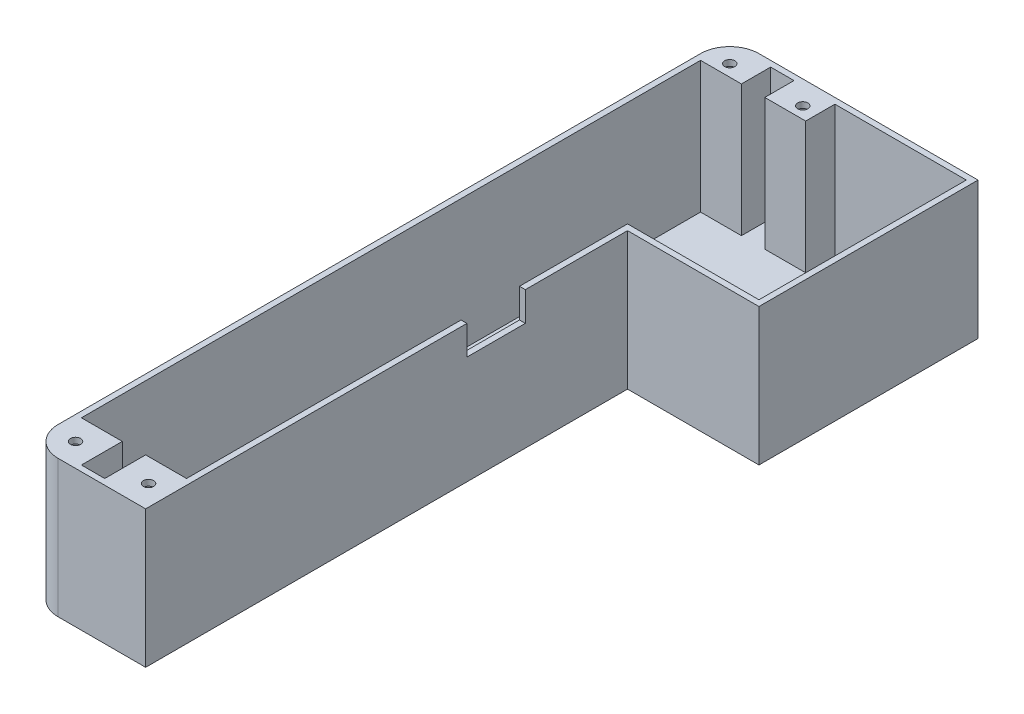
SolidWorks part; units mm, degrees
ref_plane "Front Plane" through (0, 0, 0) normal (0, 0, 1) x (1, 0, 0)
ref_plane "Top Plane" through (0, 0, 0) normal (0, 1, 0) x (1, 0, 0)
ref_plane "Right Plane" through (0, 0, 0) normal (1, 0, 0) x (0, 0, -1)
sketch "Sketch1" plane through (0, 0, 0) normal (0, 1, 0) x (1, 0, 0)
  line L1 (-20, 120) -> (20, 120)
  line L2 (-20, 120) -> (-20, -120)
  line L3 (-20, -120) -> (20, -120)
  line L4 (20, 120) -> (20, -120)
  dimension "D1" = 40
  dimension "D2" = 240
  dimension "D3" = 120
  dimension "D4" = 20
extrude "Boss-Extrude2" add sketch "Sketch1" along normal blind 2
sketch "Sketch2" plane through (0, 2, 0) normal (0, 1, 0) x (1, 0, 0)
  line L1 (20, 120) -> (-20, 120)
  line L2 (20, 120) -> (20, -120)
  line L3 (20, -120) -> (-20, -120)
  line L4 (-20, 120) -> (-20, -120)
  line L6 (18, 118) -> (-18, 118)
  line L7 (18, 118) -> (18, -118)
  line L8 (18, -118) -> (-18, -118)
  line L9 (-18, 118) -> (-18, -118)
  dimension "D1" = 36
  dimension "D2" = 236
  dimension "D3" = 2
  dimension "D4" = 2
extrude "Boss-Extrude4" add sketch "Sketch2" along normal blind 45
sketch "Sketch3" plane through (0, 2, 0) normal (0, 1, 0) x (1, 0, 0)
  line L1 (-18, 118) -> (-4, 118)
  line L2 (-18, 118) -> (-18, 104)
  line L3 (-18, 104) -> (-4, 104)
  line L4 (-4, 118) -> (-4, 104)
  line L5 (18, 118) -> (4, 118)
  line L6 (18, 118) -> (18, 104)
  line L7 (18, 104) -> (4, 104)
  line L8 (4, 118) -> (4, 104)
  line L9 (-18, -118) -> (-4, -118)
  line L10 (-18, -118) -> (-18, -104)
  line L11 (-18, -104) -> (-4, -104)
  line L12 (-4, -118) -> (-4, -104)
  line L13 (18, -118) -> (4, -118)
  line L14 (18, -118) -> (18, -104)
  line L15 (18, -104) -> (4, -104)
  line L16 (4, -118) -> (4, -104)
  dimension "D1" = 14
  dimension "D2" = 14
  dimension "D3" = 14
  dimension "D4" = 14
  dimension "D5" = 14
  dimension "D6" = 14
  dimension "D7" = 14
  dimension "D8" = 14
extrude "Boss-Extrude5" add sketch "Sketch3" along normal blind 45
sketch "Sketch4" plane through (0, 0, 0) normal (0, -1, 0) x (-1, 0, 0)
  line L0 (20, -120) -> (-20, -120) construction
  line L1 (20, 120) -> (20, -120) construction
  line L2 (-20, 120) -> (20, 120) construction
  circle A0 centre (12, -112) radius 1.75
  circle A1 centre (-13, -112) radius 1.75
  circle A2 centre (12, 112) radius 1.75
  circle A3 centre (-13, 112) radius 1.75
  dimension "D1" = 3.5
  dimension "D2" = 3.5
  dimension "D3" = 3.5
  dimension "D4" = 3.5
  dimension "D5" = 8
  dimension "D6" = 8
  dimension "D7" = 8
  dimension "D8" = 25
  dimension "D9" = 8
  dimension "D10" = 25
  dimension "D11" = 8
  dimension "D12" = 8
extrude "Cut-Extrude1" cut sketch "Sketch4" against normal blind 90
sketch "Sketch5" plane through (0, 0, 0) normal (0, -1, 0) x (-1, 0, 0)
  circle A0 centre (12, -112) radius 3.5
  circle A1 centre (-13, -112) radius 3.5
  circle A2 centre (12, 112) radius 3.5
  circle A3 centre (-13, 112) radius 3.5
  dimension "D1" = 7
  dimension "D2" = 7
  dimension "D3" = 7
  dimension "D4" = 7
extrude "Cut-Extrude2" cut sketch "Sketch5" against normal blind 45
sketch "Sketch6" plane through (20, 0, 0) normal (1, 0, 0) x (0, 0, -1)
  line L0 (-120, 47) -> (120, 47) construction
  line L1 (-10, 47) -> (10, 47)
  line L2 (-10, 47) -> (-10, 37)
  line L3 (-10, 37) -> (10, 37)
  line L4 (10, 47) -> (10, 37)
  dimension "D1" = 20
  dimension "D2" = 10
  dimension "D3" = 10
extrude "Cut-Extrude3" cut sketch "Sketch6" against normal blind 10
fillet "Fillet3" radius 10 1 edges at (-20, 23.5, -120)
fillet "Fillet4" radius 10 1 edges at (-20, 23.5, 120)
sketch "Sketch7" plane through (20, 0, 0) normal (1, 0, 0) x (0, 0, -1)
  line L0 (10, 47) -> (120, 47) construction
  line L1 (120, 0) -> (45, 0)
  line L2 (120, 0) -> (120, 47)
  line L3 (120, 47) -> (45, 47)
  line L4 (45, 0) -> (45, 47)
  dimension "D1" = 75
extrude "Boss-Extrude6" add sketch "Sketch7" along normal blind 45
sketch "Sketch8" plane through (0, 47, 0) normal (0, 1, 0) x (1, 0, 0)
  line L1 (63, 118) -> (18, 118)
  line L2 (63, 118) -> (63, 47)
  line L3 (63, 47) -> (18, 47)
  line L4 (18, 118) -> (18, 47)
  line L6 (65, 45) -> (20, 45) construction
  line L8 (65, 120) -> (65, 45) construction
  dimension "D1" = 45
  dimension "D2" = 2
  dimension "D3" = 71
  dimension "D4" = 2
extrude "Cut-Extrude4" cut sketch "Sketch8" against normal blind 45
sketch "Sketch9" plane through (0, 47, 0) normal (0, 1, 0) x (1, 0, 0)
  line L1 (18, 104) -> (-18, 104)
  line L2 (18, 104) -> (18, 108)
  line L3 (18, 108) -> (-18, 108)
  line L4 (-18, 104) -> (-18, 108)
  dimension "D1" = 4
  dimension "D2" = 36
extrude "Cut-Extrude5" cut sketch "Sketch9" against normal blind 45
